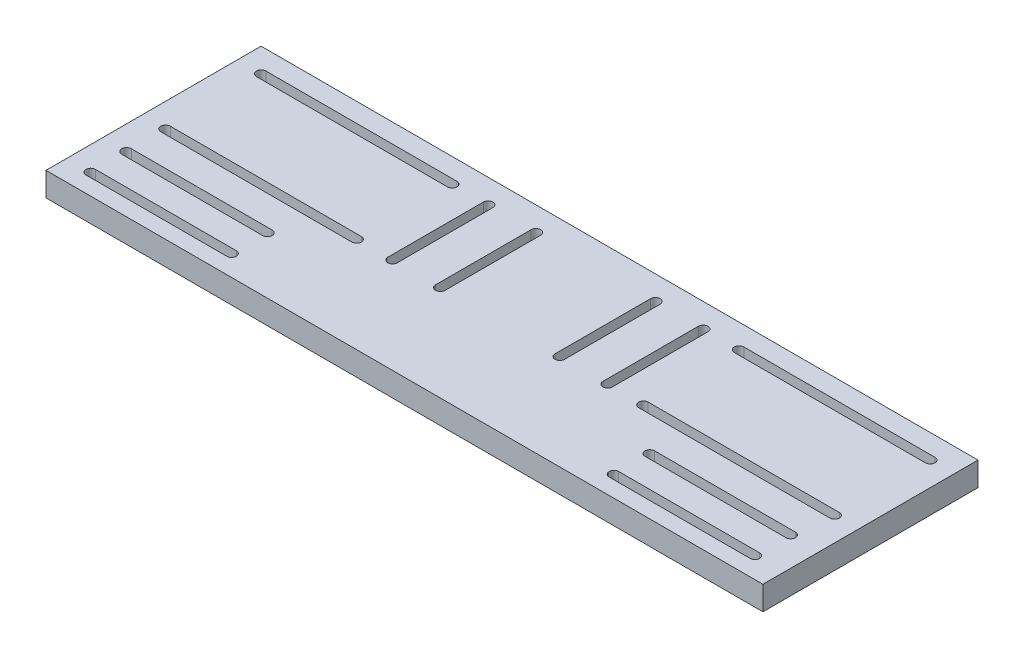
SolidWorks part; units mm, degrees
ref_plane "前视基准面" through (0, 0, 0) normal (0, 0, 1) x (1, 0, 0)
ref_plane "上视基准面" through (0, 0, 0) normal (0, 1, 0) x (1, 0, 0)
ref_plane "右视基准面" through (0, 0, 0) normal (1, 0, 0) x (0, 0, -1)
sketch "Sketch1" plane through (0, 0, 0) normal (0, 1, 0) x (1, 0, 0)
  line L0 (0, 0) -> (0, -30)
  line L1 (0, -30) -> (300, -30)
  line L2 (300, -30) -> (300, 0)
  line L3 (300, 0) -> (0, 0)
  line L4 (0, 0) -> (300, -30) construction
  line L5 (300, 0) -> (0, -30) construction
  line L6 (148.9774, 36.4033) -> (148.9774, -64.9842) construction
  line L7 (68.9774, 36.4033) -> (68.9774, -64.9842) construction
  line L8 (228.9774, 36.4033) -> (228.9774, -64.9842) construction
  line L9 (-53.4021, -13.8095) -> (322.8536, -13.8095) construction
  line L10 (-53.4021, -21.3095) -> (322.8536, -21.3095) construction
  line L11 (-53.4021, -6.3095) -> (322.8536, -6.3095) construction
  line L12 (68.9774, -6.3095) -> (10, -6.3095) construction
  line L13 (68.9774, -8.3095) -> (10, -8.3095)
  line L14 (68.9774, -4.3095) -> (10, -4.3095)
  line L15 (68.9774, -21.3095) -> (10, -21.3095) construction
  line L16 (68.9774, -23.3095) -> (10, -23.3095)
  line L17 (68.9774, -19.3095) -> (10, -19.3095)
  line L18 (228.9774, -21.3095) -> (287.9549, -21.3095) construction
  line L19 (228.9774, -23.3095) -> (287.9549, -23.3095)
  line L20 (228.9774, -19.3095) -> (287.9549, -19.3095)
  line L21 (228.9774, -6.3095) -> (287.9549, -6.3095) construction
  line L22 (228.9774, -8.3095) -> (287.9549, -8.3095)
  line L23 (228.9774, -4.3095) -> (287.9549, -4.3095)
  arc A0 (68.9774, -8.3095) -> (68.9774, -4.3095) centre (68.9774, -6.3095) ccw
  arc A1 (10, -4.3095) -> (10, -8.3095) centre (10, -6.3095) ccw
  arc A2 (68.9774, -23.3095) -> (68.9774, -19.3095) centre (68.9774, -21.3095) ccw
  arc A3 (10, -19.3095) -> (10, -23.3095) centre (10, -21.3095) ccw
  arc A4 (228.9774, -23.3095) -> (228.9774, -19.3095) centre (228.9774, -21.3095) cw
  arc A5 (287.9549, -19.3095) -> (287.9549, -23.3095) centre (287.9549, -21.3095) cw
  arc A6 (228.9774, -8.3095) -> (228.9774, -4.3095) centre (228.9774, -6.3095) cw
  arc A7 (287.9549, -4.3095) -> (287.9549, -8.3095) centre (287.9549, -6.3095) cw
  point P19 (39.4887, -6.3095)
  point P24 (39.4887, -21.3095)
  point P33 (258.4662, -21.3095)
  point P40 (258.4662, -6.3095)
  dimension "D7" = 2
  dimension "D8" = 2
  dimension "D1" = 30
  dimension "D2" = 300
  dimension "D9" = 10
  dimension "D10" = 10
  dimension "D3" = 80
  dimension "D4" = 80
  dimension "D5" = 7.5
  dimension "D6" = 7.5
extrude "Boss-Extrude1" add sketch "Sketch1" along normal blind 10
sketch "Sketch2" plane through (0, 0, 0) normal (0, 0, -1) x (-1, 0, 0)
  line L0 (-300, 10) -> (-300, 0)
  line L1 (-300, 0) -> (0, 0)
  line L2 (0, 0) -> (0, 10)
  line L3 (0, 10) -> (-300, 10)
extrude "Boss-Extrude2" add sketch "Sketch2" along normal blind 60
sketch "Sketch3" plane through (0, 10, 0) normal (0, 1, 0) x (1, 0, 0)
  line L0 (150, 110.433) -> (150, -77.7153) construction
  line L1 (10, 50) -> (90, 50) construction
  line L2 (10, 52) -> (90, 52)
  line L3 (10, 48) -> (90, 48)
  line L4 (0, 60) -> (0, -30) construction
  line L10 (0, 60) -> (300, 60) construction
  line L22 (10, 10) -> (90, 10) construction
  line L23 (10, 12) -> (90, 12)
  line L24 (10, 8) -> (90, 8)
  line L31 (125, 50) -> (125, 10) construction
  line L32 (127, 50) -> (127, 10)
  line L33 (123, 50) -> (123, 10)
  line L37 (105, 50) -> (105, 10) construction
  line L38 (107, 50) -> (107, 10)
  line L39 (103, 50) -> (103, 10)
  line L40 (290, 50) -> (210, 50) construction
  line L41 (290, 52) -> (210, 52)
  line L42 (290, 48) -> (210, 48)
  line L52 (290, 10) -> (210, 10) construction
  line L53 (290, 12) -> (210, 12)
  line L54 (290, 8) -> (210, 8)
  line L61 (175, 50) -> (175, 10) construction
  line L62 (173, 50) -> (173, 10)
  line L63 (177, 50) -> (177, 10)
  line L67 (195, 50) -> (195, 10) construction
  line L68 (193, 50) -> (193, 10)
  line L69 (197, 50) -> (197, 10)
  line L126 (10, 20) -> (90, 20) construction
  line L127 (10, 22) -> (90, 22)
  line L128 (10, 18) -> (90, 18)
  line L129 (10, 30) -> (90, 30) construction
  line L130 (10, 32) -> (90, 32)
  line L131 (10, 28) -> (90, 28)
  line L132 (10, 40) -> (90, 40) construction
  line L133 (10, 42) -> (90, 42)
  line L134 (10, 38) -> (90, 38)
  line L135 (10, 20) -> (90, 20) construction
  line L136 (10, 22) -> (90, 22)
  line L137 (10, 18) -> (90, 18)
  line L138 (10, 30) -> (90, 30) construction
  line L139 (10, 32) -> (90, 32)
  line L140 (10, 28) -> (90, 28)
  line L141 (10, 40) -> (90, 40) construction
  line L142 (10, 42) -> (90, 42)
  line L143 (10, 38) -> (90, 38)
  arc A0 (10, 52) -> (10, 48) centre (10, 50) ccw
  arc A1 (90, 48) -> (90, 52) centre (90, 50) ccw
  arc A14 (10, 12) -> (10, 8) centre (10, 10) ccw
  arc A15 (90, 8) -> (90, 12) centre (90, 10) ccw
  arc A20 (127, 50) -> (123, 50) centre (125, 50) ccw
  arc A21 (123, 10) -> (127, 10) centre (125, 10) ccw
  arc A24 (107, 50) -> (103, 50) centre (105, 50) ccw
  arc A25 (103, 10) -> (107, 10) centre (105, 10) ccw
  arc A26 (290, 52) -> (290, 48) centre (290, 50) cw
  arc A27 (210, 48) -> (210, 52) centre (210, 50) cw
  arc A34 (290, 12) -> (290, 8) centre (290, 10) cw
  arc A35 (210, 8) -> (210, 12) centre (210, 10) cw
  arc A40 (173, 50) -> (177, 50) centre (175, 50) cw
  arc A41 (177, 10) -> (173, 10) centre (175, 10) cw
  arc A44 (193, 50) -> (197, 50) centre (195, 50) cw
  arc A45 (197, 10) -> (193, 10) centre (195, 10) cw
  arc A94 (10, 22) -> (10, 18) centre (10, 20) ccw
  arc A95 (90, 18) -> (90, 22) centre (90, 20) ccw
  arc A96 (10, 32) -> (10, 28) centre (10, 30) ccw
  arc A97 (90, 28) -> (90, 32) centre (90, 30) ccw
  arc A98 (10, 42) -> (10, 38) centre (10, 40) ccw
  arc A99 (90, 38) -> (90, 42) centre (90, 40) ccw
  point P4 (50, 50)
  point P15 (109.2667, 60)
  point P16 (50, 20)
  point P30 (50, 30)
  point P37 (50, 10)
  point P51 (115, 30)
  point P58 (125, 30)
  point P65 (50, 40)
  point P72 (105, 30)
  point P78 (250, 50)
  point P106 (250, 10)
  point P127 (175, 30)
  point P141 (195, 30)
  point P148 (135, 30)
  point P155 (135, 30)
  point P162 (50, 20)
  point P169 (50, 30)
  point P176 (115, 30)
  point P183 (50, 40)
  point P190 (135, 30)
  point P197 (50, 20)
  point P204 (50, 30)
  point P211 (115, 30)
  point P218 (50, 40)
  point P225 (50, 20)
  point P232 (50, 30)
  point P239 (50, 40)
  point P246 (50, 20)
  point P253 (50, 30)
  point P260 (50, 40)
  point P267 (50, 20)
  point P274 (50, 30)
  point P281 (50, 40)
  point P288 (50, 20)
  point P295 (50, 30)
  point P302 (50, 40)
  dimension "D1" = 2
  dimension "D2" = 10
  dimension "D3" = 10
  dimension "D4" = 150
  dimension "D8" = 45
  dimension "D5" = 60
  dimension "D7" = 40
  dimension "D9" = 10
  dimension "D10" = 25
  dimension "D6" = 5
extrude "Cut-Extrude1" cut sketch "Sketch3" against normal through all
